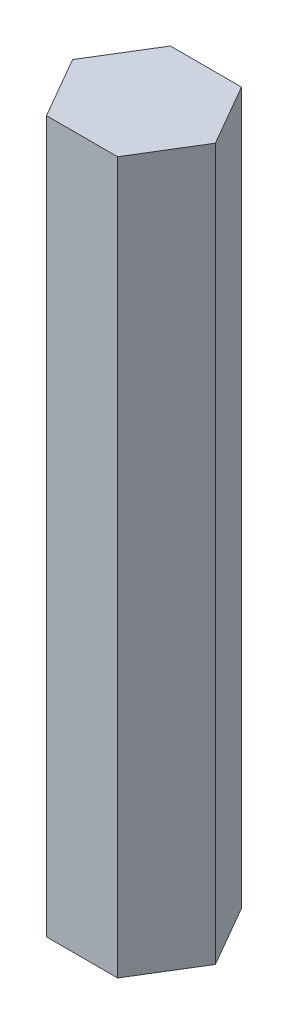
SolidWorks part; units mm, degrees
ref_plane "前视基准面" through (0, 0, 0) normal (0, 0, 1) x (1, 0, 0)
ref_plane "上视基准面" through (0, 0, 0) normal (0, 1, 0) x (1, 0, 0)
ref_plane "右视基准面" through (0, 0, 0) normal (1, 0, 0) x (0, 0, -1)
sketch "草图1" plane through (0, 0, 0) normal (0, 1, 0) x (1, 0, 0)
  line L6 (0, 0) -> (2.5, 0)
  line L7 (2.5, 0) -> (3.8054, 2.1321)
  line L8 (3.8054, 2.1321) -> (2.5561, 4.2976)
  line L9 (2.5561, 4.2976) -> (0.0561, 4.2976)
  line L10 (0.0561, 4.2976) -> (-1.2493, 2.1655)
  line L11 (-1.2493, 2.1655) -> (0, 0)
  dimension "D1" = 2.5
extrude "凸台-拉伸1" add sketch "草图1" along normal blind 25
